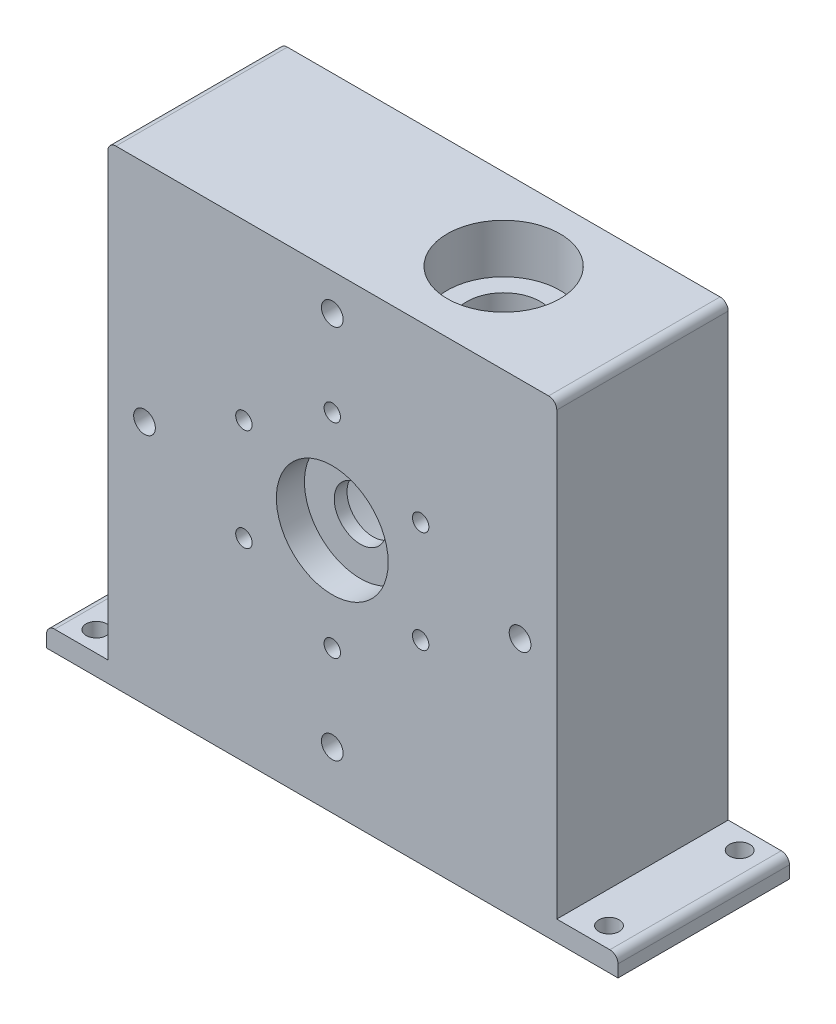
SolidWorks part; units mm, degrees
ref_plane "Front Plane" through (0, 0, 0) normal (0, 0, 1) x (1, 0, 0)
ref_plane "Top Plane" through (0, 0, 0) normal (0, 1, 0) x (1, 0, 0)
ref_plane "Right Plane" through (0, 0, 0) normal (1, 0, 0) x (0, 0, -1)
sketch "Sketch1" plane through (0, 0, 0) normal (0, 1, 0) x (1, 0, 0)
  line L1 (0, 0) -> (139.7, 0)
  line L2 (0, 0) -> (0, 12.7)
  line L3 (0, 12.7) -> (139.7, 12.7)
  line L4 (139.7, 0) -> (139.7, 12.7)
  dimension "D1" = 12.7
  dimension "D2" = 139.7
extrude "Boss-Extrude1" add sketch "Sketch1" along normal blind 146.05
sketch "Sketch2" plane through (0, 0, 0) normal (-1, 0, 0) x (0, 0, 1)
  line L0 (-12.7, 146.05) -> (-12.7, 0) construction
  line L1 (0, 0) -> (-12.7, 0)
  line L2 (0, 0) -> (0, 6.35)
  line L3 (0, 6.35) -> (-12.7, 6.35)
  line L4 (-12.7, 0) -> (-12.7, 6.35)
  dimension "D1" = 6.35
extrude "Boss-Extrude2" add sketch "Sketch2" along normal blind 19.05
ref_plane "Plane1" through (69.85, 0, 0) normal (-1, 0, 0) x (0, 0, 1)
mirror "Mirror1" about plane through (69.85, 0, 0) normal (-1, 0, 0) of "Boss-Extrude2"
sketch "Sketch3" plane through (0, 0, 0) normal (0, 0, 1) x (1, 0, 0)
  line L0 (69.85, 146.05) -> (69.85, 0) construction
  line L1 (0, 146.05) -> (139.7, 146.05) construction
  line L2 (-19.05, 0) -> (158.75, 0) construction
  circle A0 centre (69.85, 76.2) radius 17.399
  dimension "D2" = 34.798
  dimension "D1" = 76.2
sketch "Sketch6" plane through (0, 6.35, 0) normal (0, 1, 0) x (1, 0, 0)
  line L0 (0, 0) -> (0, 12.7) construction
  line L3 (0, 6.35) -> (-19.05, 6.35) construction
  line L4 (-19.05, 0) -> (-19.05, 12.7) construction
  circle A0 centre (-9.906, 6.35) radius 3.175
  dimension "D1" = 6.35
  dimension "D2" = 9.906
extrude "Cut-Extrude4" cut sketch "Sketch6" against normal up to next
mirror "Mirror2" about plane through (69.85, 0, 0) normal (-1, 0, 0) of "Cut-Extrude4"
fillet "Fillet1" radius 2.54 4 edges at (158.75, 6.35, -6.35) (-19.05, 6.35, -6.35) (139.7, 146.05, -6.35) (0, 146.05, -6.35)
extrude "Cut-Extrude5" cut sketch "Sketch3" against normal blind 8.7312 contours A0
sketch "Sketch7" plane through (0, 0, -8.7312) normal (0, 0, 1) x (1, 0, 0)
  circle A0 centre (69.85, 76.2) radius 8.128
  circle A1 centre (69.85, 76.2) radius 17.399 construction
  dimension "D1" = 16.256
extrude "Cut-Extrude6" cut sketch "Sketch7" against normal up to next contours A0
sketch "Sketch8" plane through (0, 0, -12.7) normal (0, 0, -1) x (-1, 0, 0)
  line L7 (-137.16, 146.05) -> (-2.54, 146.05)
  line L8 (-139.7, 143.51) -> (-139.7, 6.35)
  line L10 (0, 6.35) -> (0, 143.51)
  line L11 (-139.7, 6.35) -> (-156.21, 6.35)
  line L12 (-158.75, 3.81) -> (-158.75, 0)
  line L13 (-158.75, 0) -> (19.05, 0)
  line L14 (19.05, 0) -> (19.05, 3.81)
  line L15 (16.51, 6.35) -> (0, 6.35)
  arc A2 (-2.54, 146.05) -> (0, 143.51) centre (-2.54, 143.51) cw
  arc A3 (-139.7, 143.51) -> (-137.16, 146.05) centre (-137.16, 143.51) cw
  arc A4 (16.51, 6.35) -> (19.05, 3.81) centre (16.51, 3.81) cw
  arc A5 (-158.75, 3.81) -> (-156.21, 6.35) centre (-156.21, 3.81) cw
  circle A6 centre (-69.85, 76.2) radius 8.128 construction
  circle A7 centre (-69.85, 76.2) radius 44.45
  point P9 (-69.85, 76.2)
  dimension "D1" = 88.9
extrude "Boss-Extrude3" add sketch "Sketch8" along normal blind 40.64
sketch "Sketch10" plane through (0, 146.05, 0) normal (0, 1, 0) x (1, 0, 0)
  line L0 (69.85, 0) -> (69.85, 53.34) construction
  line L2 (114.3, 53.34) -> (114.3, 0) construction
  line L3 (2.54, 0) -> (137.16, 0) construction
  line L4 (2.54, 53.34) -> (137.16, 53.34) construction
  circle A0 centre (95.2246, 27.94) radius 11.4554
  point P2 (95.2246, 16.4846)
  point P12 (106.68, 27.94)
  point P13 (114.3, 53.34)
  dimension "D3" = 22.9108
  dimension "D1" = 16.4846
  dimension "D2" = 25.4
  dimension "D4" = 7.62
  dimension "D5" = 19.0754
  dimension "D6" = 25.3746
extrude "Outlet" cut sketch "Sketch10" against normal up to next contours A0
sketch "Sketch11" plane through (0, 0, -53.34) normal (0, 0, -1) x (-1, 0, 0)
  circle A0 centre (-69.85, 76.2) radius 50.3047
  circle A1 centre (-69.85, 76.2) radius 44.45 construction
  circle A2 centre (-69.85, 76.2) radius 52.4383
  dimension "D1" = 104.8766
  dimension "D2" = 2.1336
extrude "Cut-Extrude9" cut sketch "Sketch11" against normal blind 1.3208
ref_plane "Plane2" through (0, 0, -26.67) normal (0, 0, -1) x (-1, 0, 0)
mirror "Mirror3" about plane through (0, 0, -26.67) normal (0, 0, -1) of "Mirror2", "Cut-Extrude4"
sketch "Sketch12" plane through (0, 0, -12.7) normal (0, 0, -1) x (-1, 0, 0)
  line L0 (-69.85, 95.25) -> (-69.85, 57.15) construction
  line L1 (-88.9, 95.25) -> (-50.8, 95.25) construction
  line L2 (-88.9, 95.25) -> (-88.9, 57.15) construction
  line L3 (-88.9, 57.15) -> (-50.8, 57.15) construction
  line L4 (-50.8, 95.25) -> (-50.8, 57.15) construction
  line L5 (-88.9, 76.2) -> (-50.8, 76.2) construction
  circle A0 centre (-69.85, 76.2) radius 8.128 construction
  circle A1 centre (-88.9, 95.25) radius 3.175
  circle A2 centre (-50.8, 95.25) radius 3.175
  circle A3 centre (-50.8, 57.15) radius 3.175
  circle A4 centre (-88.9, 57.15) radius 3.175
  point P8 (-69.85, 76.2)
  dimension "D2" = 6.35
  dimension "D1" = 38.1
  dimension "D3" = 2
  dimension "D4" = 2
extrude "Cut-Extrude10" cut sketch "Sketch12" against normal blind 2.54
fillet "Fillet2" radius 0.127 2 edges at (19.5453, 76.2, -53.34) (17.4117, 76.2, -53.34)
fillet "Fillet3" radius 0.254 2 edges at (19.5453, 76.2, -52.0192) (17.4117, 76.2, -52.0192)
sketch "Sketch13" plane through (0, 0, -53.34) normal (0, 0, -1) x (-1, 0, 0)
  line L0 (-69.85, 76.2) -> (-128.27, 76.2) construction
  line L1 (-69.85, 76.2) -> (-69.85, 134.62) construction
  circle A0 centre (-69.85, 76.2) radius 58.42 construction
  circle A1 centre (-128.27, 76.2) radius 3.3782
  circle A2 centre (-69.85, 134.62) radius 3.3782
  circle A3 centre (-11.43, 76.2) radius 3.3782
  circle A4 centre (-69.85, 17.78) radius 3.3782
  point P14 (-69.85, 76.2)
  dimension "D1" = 116.84
  dimension "D3" = 6.7564
  dimension "D2" = 90
  dimension "D4" = 4
extrude "Cut-Extrude11" cut sketch "Sketch13" against normal through all
sketch "Sketch14" plane through (0, 146.05, 0) normal (0, 1, 0) x (1, 0, 0)
  circle A0 centre (95.2246, 27.94) radius 17.526
  circle A1 centre (95.2246, 27.94) radius 11.4554 construction
  dimension "D1" = 35.052
extrude "Cut-Extrude12" cut sketch "Sketch14" against normal blind 15.24
sketch "Sketch17" plane through (0, 0, 0) normal (0, 0, 1) x (1, 0, 0)
  line L0 (69.85, 76.2) -> (69.85, 107.95) construction
  line L1 (69.85, 76.2) -> (97.3463, 92.075) construction
  line L2 (69.85, 76.2) -> (97.3463, 60.325) construction
  line L3 (69.85, 76.2) -> (69.85, 44.45) construction
  line L4 (69.85, 76.2) -> (42.3537, 60.325) construction
  line L5 (69.85, 76.2) -> (42.3537, 92.075) construction
  circle A0 centre (69.85, 76.2) radius 31.75 construction
  point P11 (69.85, 76.2)
  dimension "D1" = 63.5
  dimension "D2" = 6
hole_wizard "Tap Drill for 1/4-20 Tap1" positions "3DSketch1" profile "Sketch19" hole size "1/4-20" standard "ANSI Inch"
sketch3d "3DSketch1"
  line L0 (69.85, 76.2, 0) -> (42.3537, 60.325, 0) construction
  point P0 (69.85, 107.95, 0)
  point P3 (97.3463, 92.075, 0)
  point P6 (97.3463, 60.325, 0)
  point P9 (69.85, 44.45, 0)
  point P12 (42.3537, 60.325, 0)
  point P16 (42.3537, 92.075, 0)
  point P20 (39.2331, 58.5233, 0)
  point P21 (42.3537, 60.325, 0)
sketch "Sketch19" plane through (69.85, 107.95, 0) normal (1, 0, 0) x (0, -1, 0)
  line L0 (0, 0) -> (0, 10.16)
  line L1 (0, 10.16) -> (2.5527, 8.6262)
  line L2 (2.5527, 8.6262) -> (2.5527, 0)
  line L5 (2.5527, 0) -> (0, 0)
  line L10 (0, 10.16) -> (-2.5527, 8.6262) construction
  line L11 (0, -6.35) -> (0, 107.95) construction
  dimension "Hole Dia." = 5.1054
  dimension "Hole Depth" = 10.16
  dimension "Drill Angle" = 118
